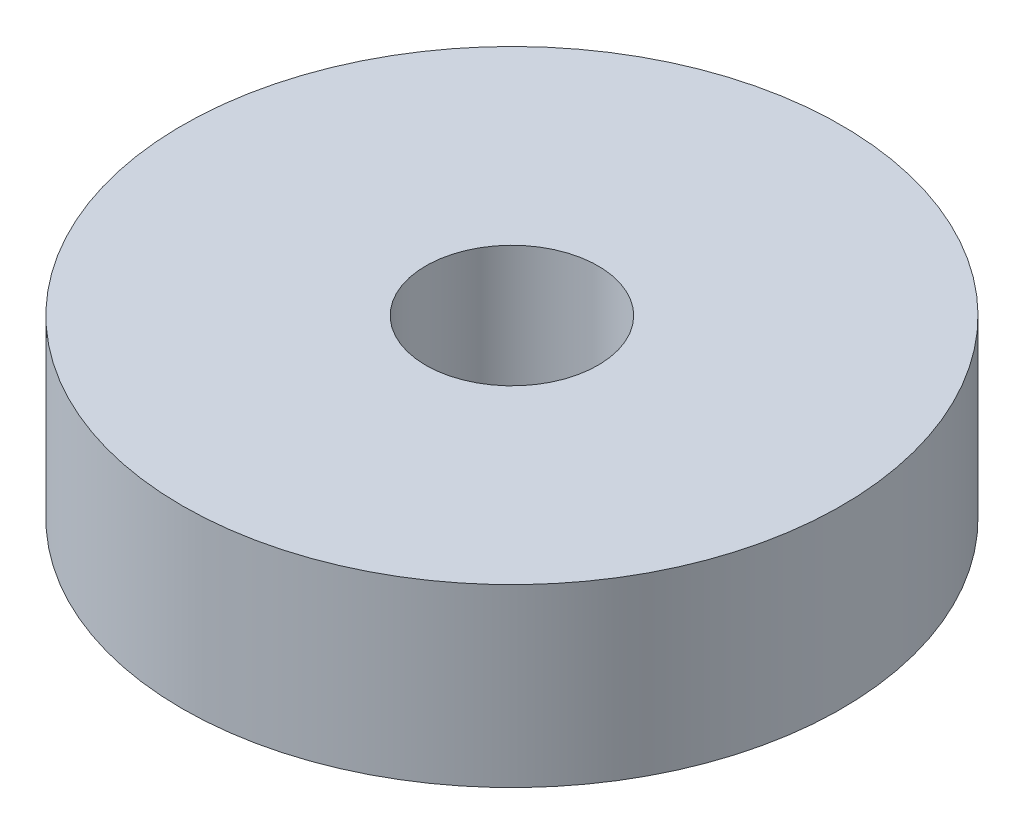
SolidWorks part; units mm, degrees
material "PTFE (general)"
ref_plane "Front Plane" through (0, 0, 0) normal (0, 0, 1) x (1, 0, 0)
ref_plane "Top Plane" through (0, 0, 0) normal (0, 1, 0) x (1, 0, 0)
ref_plane "Right Plane" through (0, 0, 0) normal (1, 0, 0) x (0, 0, -1)
sketch "Sketch1" plane through (0, 0, 0) normal (0, 1, 0) x (1, 0, 0)
  circle A0 centre (0, 0) radius 9.525
  dimension "D1" = 19.05
extrude "Boss-Extrude1" add sketch "Sketch1" along normal blind 5.08
hole_wizard "#10 Clearance Hole1" positions "Sketch2" profile "Sketch3" hole size "#10" standard "ANSI Inch" end condition through all
sketch "Sketch2" plane through (0, 5.08, 0) normal (0, 1, 0) x (1, 0, 0)
  point P0 (0, 0)
  point P3 (0, 0)
  point P4 (0, 0)
sketch "Sketch3" plane through (0, 5.08, 0) normal (1, 0, 0) x (0, 0, 1)
  line L0 (0, 0) -> (0, 5.08)
  line L1 (0, 5.08) -> (2.4892, 5.08)
  line L2 (2.4892, 5.08) -> (2.4892, 0)
  line L5 (2.4892, 0) -> (0, 0)
  line L11 (0, -6.35) -> (0, 107.95) construction
  dimension "Thru Hole Dia." = 4.9784
  dimension "Thru Hole Depth" = 5.08
